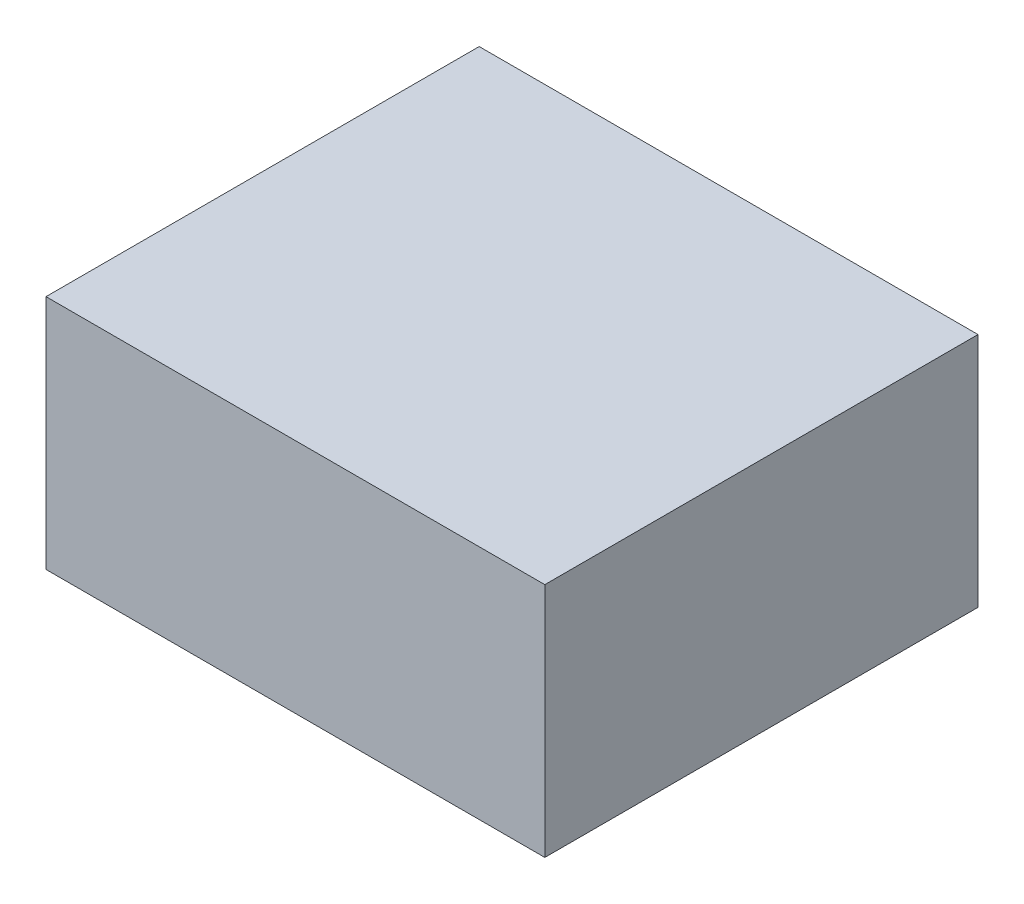
SolidWorks part; units mm, degrees
ref_plane "前视基准面" through (0, 0, 0) normal (0, 0, 1) x (1, 0, 0)
ref_plane "上视基准面" through (0, 0, 0) normal (0, 1, 0) x (1, 0, 0)
ref_plane "右视基准面" through (0, 0, 0) normal (1, 0, 0) x (0, 0, -1)
other "Configuration Table"
sketch "草图1" plane through (0, 0, 0) normal (0, 1, 0) x (1, 0, 0)
  line L1 (0, 0) -> (38, 0)
  line L2 (0, 0) -> (0, -33)
  line L3 (0, -33) -> (38, -33)
  line L4 (38, 0) -> (38, -33)
  dimension "D1" = 33
  dimension "D2" = 38
extrude "凸台-拉伸1" add sketch "草图1" along normal blind 18
